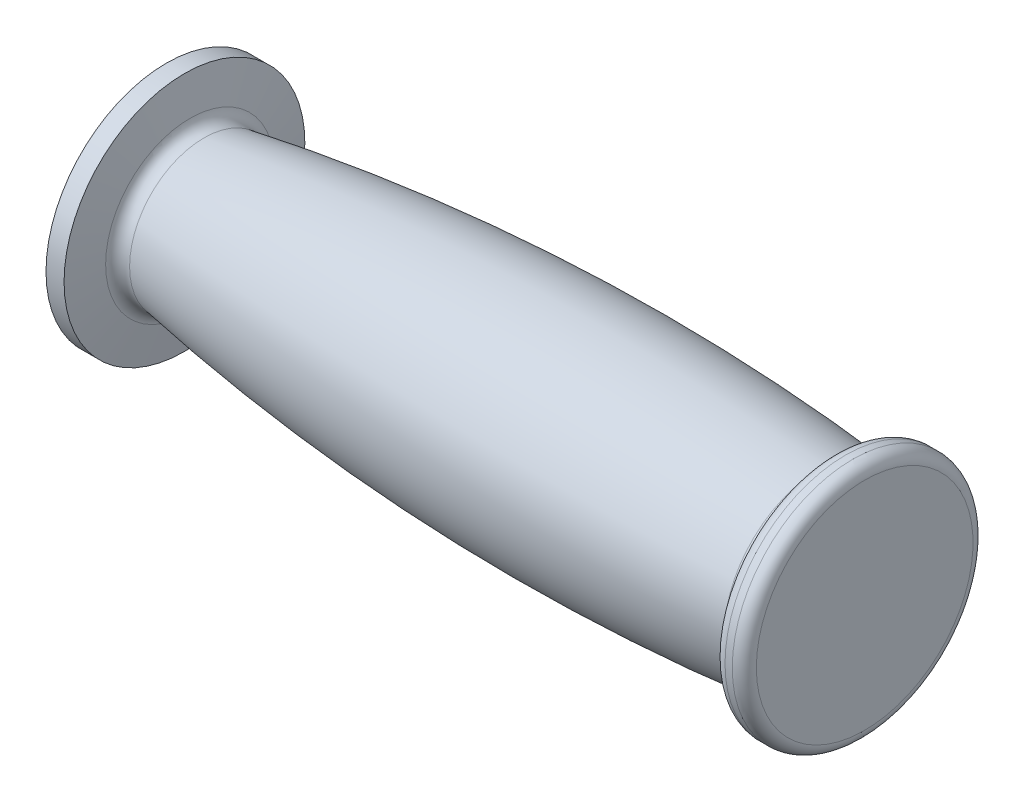
SolidWorks part; units mm, degrees
ref_plane "Ebene vorne" through (0, 0, 0) normal (0, 0, 1) x (1, 0, 0)
ref_plane "Ebene oben" through (0, 0, 0) normal (0, 1, 0) x (1, 0, 0)
ref_plane "Ebene rechts" through (0, 0, 0) normal (1, 0, 0) x (0, 0, -1)
sketch "Skizze1" plane through (0, 0, 0) normal (0, 0, 1) x (1, 0, 0)
  line L0 (0, 0) -> (44779.7325, 0) construction
  line L1 (0, 0) -> (0, 5)
  line L2 (0, 5) -> (5, 5)
  line L3 (5, 5) -> (5, 7)
  line L4 (5, 7) -> (7, 7)
  line L5 (7, 7) -> (9, 20)
  line L6 (9, 20) -> (12, 20)
  line L7 (12, 20) -> (13.2308, 12)
  line L8 (119.5494, 15.7127) -> (120, 20)
  line L10 (125, 0) -> (0, 0)
  line L11 (10.5, 11.6629) -> (10.5, -49988.3371) construction
  line L12 (13.1218, 11.9808) -> (49253.5094, 8694.3897) construction
  line L13 (85.6349, 19.2773) -> (-36634.0123, 3878.6677) construction
  line L14 (14.031, 12) -> (50014.031, 12) construction
  line L15 (98.3986, 15.7127) -> (-49901.6014, 15.7127) construction
  line L16 (120, 20) -> (125, 20)
  line L17 (125, 20) -> (125, 0)
  arc A0 (13.2308, 12) -> (119.5494, 15.7127) centre (79.5988, -364.3918) cw
  point P13 (83.5432, 8.563)
  point P18 (10.5, 20)
  point P28 (71.8274, 9.5248)
  point P29 (97.0111, 10.6243)
  point P30 (98.732, 9.9589)
  point P31 (14, 7)
  point P32 (98.8502, 9.963)
  point P33 (13.1998, 12.2012)
  dimension "D1" = 10
  dimension "D2" = 5
  dimension "D3" = 2
  dimension "D4" = 20
  dimension "D5" = 7
  dimension "D6" = 3
  dimension "D7" = 4
  dimension "D8" = 10
  dimension "D9" = 6
  dimension "D10" = 5
  dimension "D11" = 120
  dimension "D12" = 90
  dimension "D13" = 12
revolve "Rotation1" add sketch "Skizze1" angle 360 about L0
fillet "Verrundung2" radius 2 4 edges at (13.2308, 0, 12) (125, 0, 20) (120, 0, 20) (119.5494, 0, 15.7127)
